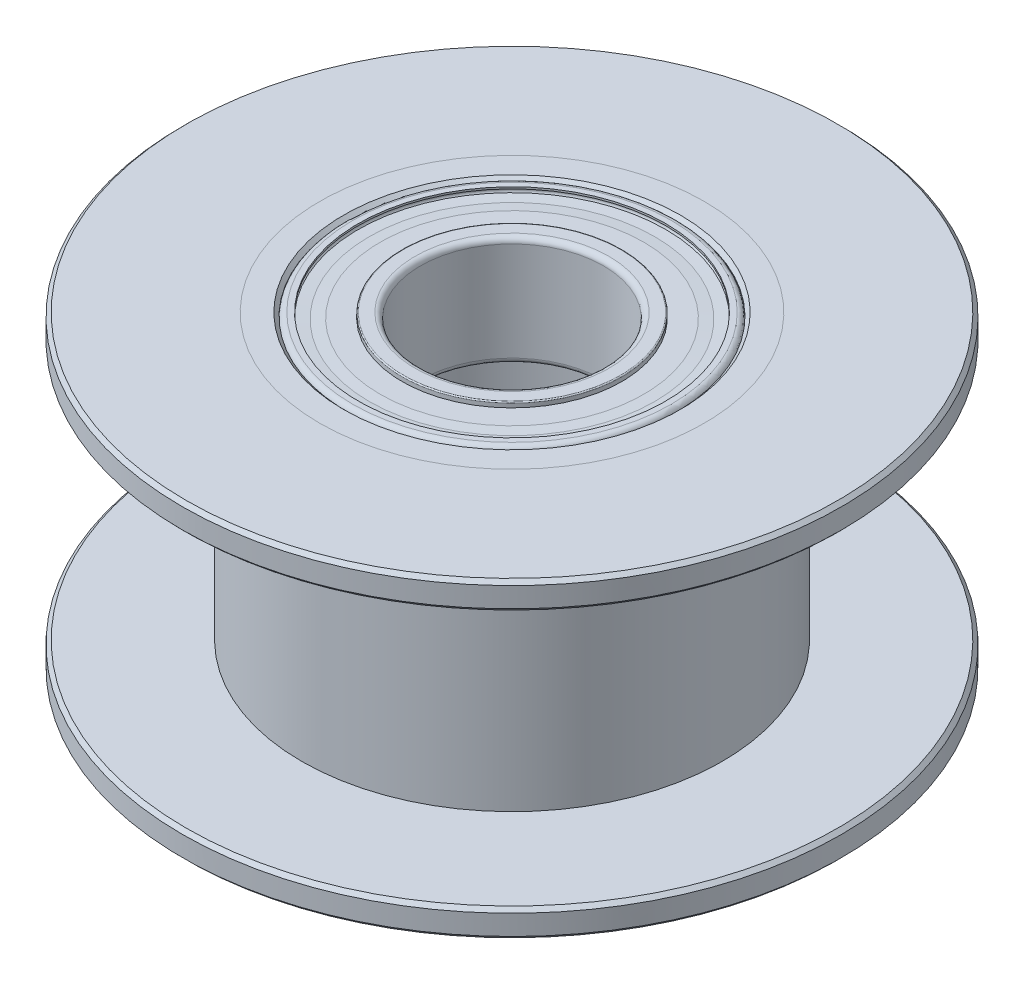
SolidWorks part; units mm, degrees
material "6061-T6 (SS)"
ref_plane "Přední rovina" through (0, 0, 0) normal (0, 0, 1) x (1, 0, 0)
ref_plane "Horní rovina" through (0, 0, 0) normal (0, 1, 0) x (1, 0, 0)
ref_plane "Pravá rovina" through (0, 0, 0) normal (1, 0, 0) x (0, 0, -1)
sketch "Skica1" plane through (0, 0, 0) normal (0, 0, 1) x (1, 0, 0)
  line L0 (4.5, 8.5) -> (5.25, 8.5)
  line L1 (5.25, 8.5) -> (5.25, 7.75)
  line L2 (5.25, 7.75) -> (6.11, 7.75)
  line L3 (6.11, 7.75) -> (6.11, 0.75)
  line L4 (6.11, 0.75) -> (5.25, 0.75)
  line L5 (5.25, 0.75) -> (5.25, 0)
  line L6 (5.25, 0) -> (4.5, 0)
  line L8 (4.5, 8.5) -> (4.5, 5.5)
  line L9 (4.5, 5.5) -> (3.5, 5.5)
  line L10 (3.5, 5.5) -> (3.5, 3)
  line L11 (3.5, 3) -> (4.5, 3)
  line L12 (4.5, 3) -> (4.5, 0)
  line L13 (0, 0) -> (0, -4.1646) construction
  dimension "D1" = 8.5
  dimension "D2" = 7
  dimension "D3" = 4.5
  dimension "D4" = 3.5
  dimension "D5" = 6.11
  dimension "D6" = 3
  dimension "D7" = 5.25
revolve "Rotovat1" add sketch "Skica1" angle 360 about L13
chamfer "Zkosení1" distance 0.1 angle 45 4 edges at (0, 3, 3.5) (0, 0, 4.5) (0, 5.5, 3.5) (0, 8.5, 4.5)
fillet "Zaoblit1" radius 0.1 2 edges at (0, 3, 4.5) (0, 5.5, 4.5)
sketch "Skica11" plane through (0, 7.75, 0) normal (0, 1, 0) x (1, 0, 0)
  circle A0 centre (0, 0) radius 5.7444
extrude "Odebrat vysunutím1" cut sketch "Skica11" against normal through all flip side to cut
sketch "Skica10" plane through (0, 8.5, 0) normal (0, 1, 0) x (1, 0, 0)
  circle A0 centre (0, 0) radius 9
  circle A1 centre (0, 0) radius 5.25 construction
  circle A2 centre (0, 0) radius 5.25
  dimension "D1" = 18
extrude "Přidat vysunutím1" add sketch "Skica10" against normal up to surface (0.75 mm away) separate body up to face at (0, 7.75, 5.25)
sketch "Skica12" plane through (0, 0, 0) normal (0, -1, 0) x (1, 0, 0)
  circle A0 centre (0, 0) radius 9
  circle A1 centre (0, 0) radius 5.25 construction
  circle A2 centre (0, 0) radius 5.25
  circle A3 centre (0, 0) radius 9 construction
extrude "Přidat vysunutím2" add sketch "Skica12" against normal up to surface (0.75 mm away) separate body up to face at (0, 0.75, 5.25)
chamfer "Zkosení2" distance 0.1 angle 45 2 edges at (0, 7.75, -9) (0, 8.5, 9)
chamfer "Zkosení3" distance 0.1 angle 45 2 edges at (0, 0, -9) (0, 0.75, 9)
sketch "Skica4" plane through (0, 0, 0) normal (0, 0, 1) x (1, 0, 0)
  line L0 (4.5, 8.35) -> (4.5, 5.65)
  line L1 (4.35, 5.5) -> (4.2, 5.5)
  line L2 (4.2, 5.5) -> (4.2, 5.55)
  line L3 (3.85, 5.7828) -> (4.2132, 5.729)
  line L4 (3.85, 5.7828) -> (3.85, 6.5528)
  line L5 (3.85, 7.4472) -> (3.85, 8.2172)
  line L6 (3.85, 8.2172) -> (4.2132, 8.271)
  line L7 (4.35, 8.5) -> (4.2, 8.5)
  line L8 (4.2, 8.5) -> (4.2, 8.45)
  line L9 (0, 0) -> (0, 18.4294) construction
  line L10 (4.4, 5.5) -> (-4.4, 5.5) construction
  arc A0 (4.35, 8.5) -> (4.5, 8.35) centre (4.35, 8.35) cw
  arc A1 (4.35, 5.5) -> (4.5, 5.65) centre (4.35, 5.65) ccw
  arc A2 (4.2, 8.45) -> (4.2132, 8.271) centre (4.2, 8.36) cw
  arc A3 (3.85, 7.4472) -> (3.85, 6.5528) centre (3.45, 7) cw
  arc A4 (4.2, 5.55) -> (4.2132, 5.729) centre (4.2, 5.64) ccw
  point P26 (4.5, 7)
  point P29 (4.275, 5.5)
  dimension "D3" = 0.09
  dimension "D6" = 0.15
  dimension "D7" = 0.6
  dimension "D1" = 4.5
  dimension "D2" = 3.85
  dimension "D4" = 0.05
  dimension "D5" = 0.15
  dimension "D8" = 0.77
  dimension "D9" = 3
  dimension "D10" = 1.05
revolve "Rotovat2" add sketch "Skica4" angle 360 about L9
sketch "Skica5" plane through (0, 0, 0) normal (0, 0, 1) x (1, 0, 0)
  line L0 (2.5, 8.35) -> (2.5, 5.65)
  line L1 (2.65, 8.5) -> (2.97, 8.5)
  line L2 (3, 8.47) -> (3, 8.36)
  line L3 (3, 8.36) -> (3.6, 8.36)
  line L4 (3.6, 8.36) -> (3.9, 8.34)
  line L5 (3.9, 8.34) -> (4.2, 8.36)
  line L6 (4.2, 8.36) -> (4.2, 8.31)
  line L7 (4.2, 8.31) -> (3.9, 8.27)
  line L8 (3.9, 8.27) -> (3.6, 8.27)
  line L9 (3.6, 8.27) -> (3, 8.31)
  line L10 (3, 8.31) -> (3, 7.3969)
  line L11 (2.65, 5.5) -> (2.97, 5.5)
  line L12 (0, 0) -> (0, 20.363) construction
  line L13 (3, 5.53) -> (3, 5.64)
  line L21 (3, 5.69) -> (3, 6.6031)
  line L22 (3, 5.64) -> (3.6, 5.64)
  line L23 (3.6, 5.64) -> (3.8962, 5.6917)
  line L24 (3.8962, 5.6917) -> (4.1924, 5.64)
  line L25 (4.1924, 5.64) -> (4.1924, 5.69)
  line L26 (4.1924, 5.69) -> (3.8975, 5.7581)
  line L27 (3.8975, 5.7581) -> (3.5975, 5.7581)
  line L28 (3.5975, 5.7581) -> (3, 5.69)
  line L29 (-4.2, 5.5) -> (4.2, 5.5) construction
  arc A0 (2.65, 5.5) -> (2.5, 5.65) centre (2.65, 5.65) cw
  arc A1 (2.65, 8.5) -> (2.5, 8.35) centre (2.65, 8.35) ccw
  arc A2 (3, 8.47) -> (2.97, 8.5) centre (2.97, 8.47) ccw
  arc A3 (3, 5.53) -> (2.97, 5.5) centre (2.97, 5.53) cw
  arc A4 (3, 7.3969) -> (3, 6.6031) centre (3.45, 7) ccw
  dimension "D3" = 0.15
  dimension "D4" = 0.11
  dimension "D5" = 0.03
  dimension "D7" = 0.6
  dimension "D1" = 2.5
  dimension "D2" = 3
  dimension "D6" = 0.6
  dimension "D8" = 0.95
  dimension "D9" = 3
  dimension "D10" = 1.2
  dimension "D11" = 0.3
  dimension "D12" = 0.05
  dimension "D13" = 0.9
  dimension "D14" = 0.6
  dimension "D15" = 0.09
  dimension "D16" = 0.05
  dimension "D17" = 0.05
revolve "Rotovat3" add sketch "Skica5" angle 360 about L12
sketch "Skica6" plane through (0, 0, 0) normal (0, 0, 1) x (1, 0, 0)
  line L0 (3.45, 7.6) -> (3.45, 6.4)
  line L4 (-4.2, 5.5) -> (4.2, 5.5) construction
  arc A0 (3.45, 7.6) -> (3.45, 6.4) centre (3.45, 7) cw
  dimension "D1" = 0.6
  dimension "D2" = 1.5
  dimension "D3" = 3.45
revolve "Rotovat4" add sketch "Skica6" angle 360 about L0
pattern_circular "Kruhové pole1" count 8 over 360 about axis through (0, 0, 0) along (0, 1, 0) of bodies 105
sketch "Skica7" plane through (0, 0, 0) normal (0, 0, 1) x (1, 0, 0)
  line L0 (4.5, 2.85) -> (4.5, 0.15)
  line L1 (4.35, 0) -> (4.2, 0)
  line L2 (4.2, 0) -> (4.2, 0.05)
  line L3 (3.85, 0.2828) -> (4.2132, 0.229)
  line L4 (3.85, 0.2828) -> (3.85, 1.0528)
  line L5 (3.85, 1.9472) -> (3.85, 2.7172)
  line L6 (3.85, 2.7172) -> (4.2132, 2.771)
  line L7 (4.35, 3) -> (4.2, 3)
  line L8 (4.2, 3) -> (4.2, 2.95)
  line L9 (0, 0) -> (0, 11.2374) construction
  arc A0 (4.35, 3) -> (4.5, 2.85) centre (4.35, 2.85) cw
  arc A1 (4.35, 0) -> (4.5, 0.15) centre (4.35, 0.15) ccw
  arc A2 (4.2, 2.95) -> (4.2132, 2.771) centre (4.2, 2.86) cw
  arc A3 (3.85, 1.9472) -> (3.85, 1.0528) centre (3.45, 1.5) cw
  arc A4 (4.2, 0.05) -> (4.2132, 0.229) centre (4.2, 0.14) ccw
  point P19 (4.5, 1.5)
  point P20 (4.275, 0)
  dimension "D1" = 0.09
  dimension "D4" = 0.15
  dimension "D5" = 0.6
  dimension "D2" = 0.05
  dimension "D3" = 0.15
  dimension "D6" = 0.77
  dimension "D7" = 3
  dimension "D8" = 1.05
  dimension "D9" = 4.5
  dimension "D10" = 3.85
revolve "Rotovat5" add sketch "Skica7" angle 360 about L9
sketch "Skica8" plane through (0, 0, 0) normal (0, 0, 1) x (1, 0, 0)
  line L0 (2.5, 2.85) -> (2.5, 0.15)
  line L1 (2.65, 3) -> (2.97, 3)
  line L2 (3, 2.97) -> (3, 2.86)
  line L3 (3, 2.86) -> (3.6, 2.86)
  line L4 (3.6, 2.86) -> (3.9, 2.84)
  line L5 (3.9, 2.84) -> (4.2, 2.86)
  line L6 (4.2, 2.86) -> (4.2, 2.81)
  line L7 (4.2, 2.81) -> (3.9, 2.77)
  line L8 (3.9, 2.77) -> (3.6, 2.77)
  line L9 (3.6, 2.77) -> (3, 2.81)
  line L10 (3, 2.81) -> (3, 1.8969)
  line L11 (2.65, 0) -> (2.97, 0)
  line L12 (3, 0.03) -> (3, 0.14)
  line L13 (3, 0.19) -> (3, 1.1031)
  line L14 (3, 0.14) -> (3.6, 0.14)
  line L15 (3.6, 0.14) -> (3.8962, 0.1917)
  line L16 (3.8962, 0.1917) -> (4.1924, 0.14)
  line L17 (4.1924, 0.14) -> (4.1924, 0.19)
  line L18 (4.1924, 0.19) -> (3.8975, 0.2581)
  line L19 (3.8975, 0.2581) -> (3.5975, 0.2581)
  line L20 (3.5975, 0.2581) -> (3, 0.19)
  line L21 (0, 0) -> (0, -2.9362) construction
  arc A0 (2.65, 0) -> (2.5, 0.15) centre (2.65, 0.15) cw
  arc A1 (2.65, 3) -> (2.5, 2.85) centre (2.65, 2.85) ccw
  arc A2 (3, 2.97) -> (2.97, 3) centre (2.97, 2.97) ccw
  arc A3 (3, 0.03) -> (2.97, 0) centre (2.97, 0.03) cw
  arc A4 (3, 1.8969) -> (3, 1.1031) centre (3.45, 1.5) ccw
  dimension "D1" = 0.15
  dimension "D2" = 0.03
  dimension "D5" = 0.6
  dimension "D3" = 0.11
  dimension "D4" = 0.6
  dimension "D6" = 0.95
  dimension "D7" = 3
  dimension "D8" = 1.2
  dimension "D9" = 0.3
  dimension "D10" = 0.05
  dimension "D11" = 0.9
  dimension "D12" = 0.6
  dimension "D13" = 0.09
  dimension "D14" = 0.05
  dimension "D15" = 0.05
  dimension "D16" = 2.5
  dimension "D17" = 3
revolve "Rotovat6" add sketch "Skica8" angle 360 about L21
sketch "Skica9" plane through (0, 0, 0) normal (0, 0, 1) x (1, 0, 0)
  line L0 (3.45, 2.1) -> (3.45, 0.9)
  line L1 (0, -2.351) -> (0, 5.6956) construction
  arc A0 (3.45, 2.1) -> (3.45, 0.9) centre (3.45, 1.5) cw
  dimension "D1" = 0.6
  dimension "D2" = 3.45
  dimension "D3" = 1.5
revolve "Rotovat7" add sketch "Skica9" angle 360 about L0
pattern_circular "Kruhové pole3" count 8 over 360 about axis through (0, 0, 0) along (0, 1, 0) of bodies 123
